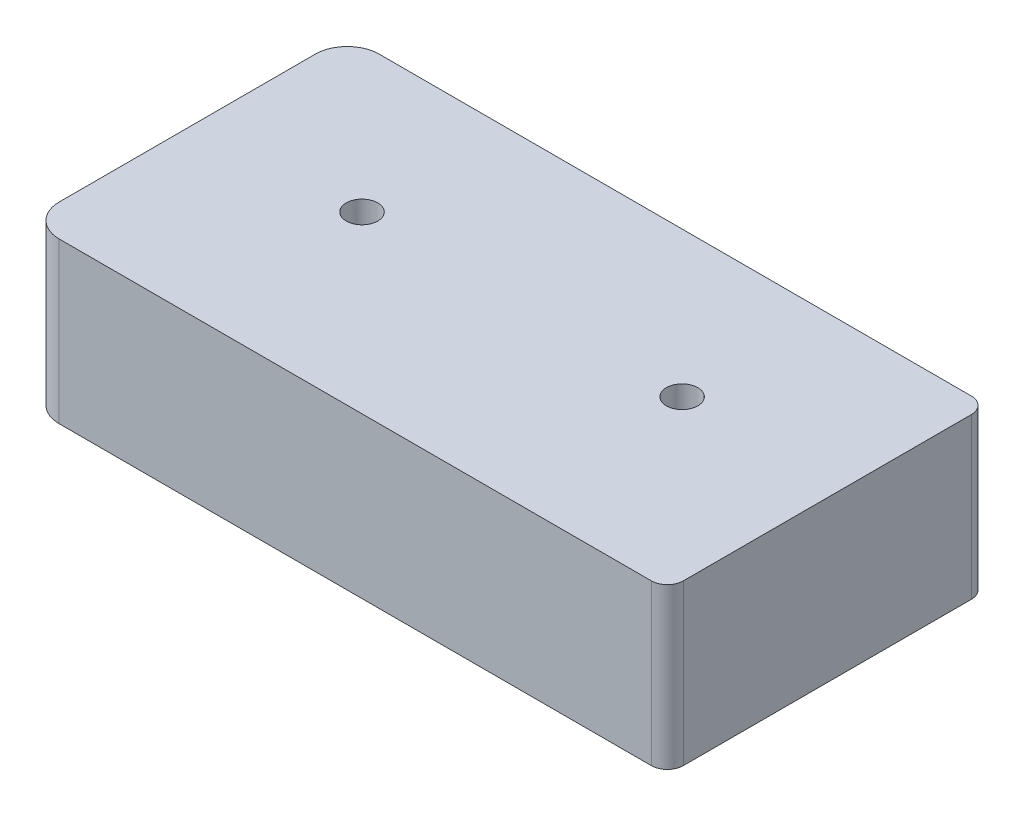
SolidWorks part; units mm, degrees
ref_plane "Front Plane" through (0, 0, 0) normal (0, 0, 1) x (1, 0, 0)
ref_plane "Top Plane" through (0, 0, 0) normal (0, 1, 0) x (1, 0, 0)
ref_plane "Right Plane" through (0, 0, 0) normal (1, 0, 0) x (0, 0, -1)
sketch "Sketch1" plane through (0, 0, 0) normal (0, 1, 0) x (1, 0, 0)
  line L1 (-50.8, 23.0573) -> (50.8, 23.0573)
  line L2 (-50.8, 23.0573) -> (-50.8, -27.7427)
  line L3 (-50.8, -27.7427) -> (50.8, -27.7427)
  line L4 (50.8, 23.0573) -> (50.8, -27.7427)
  point P4 (0, -27.7427)
  dimension "D1" = 50.8
  dimension "D2" = 101.6
extrude "Boss-Extrude1" add sketch "Sketch1" along normal blind 25.4
fillet "Fillet1" radius 5.08 2 edges at (-50.8, 12.7, 27.7427) (-50.8, 12.7, -23.0573)
fillet "Fillet2" radius 2.54 2 edges at (50.8, 12.7, 27.7427) (50.8, 12.7, -23.0573)
sketch "Sketch2" plane through (0, 25.4, 0) normal (0, 1, 0) x (1, 0, 0)
  line L0 (-50.8, 17.9773) -> (-50.8, -22.6627) construction
  line L1 (50.8, -25.2027) -> (50.8, 20.5173) construction
  circle A0 centre (-25.4, 0) radius 2.5
  circle A1 centre (25.4, 0) radius 2.5
  dimension "D1" = 5
  dimension "D2" = 25.4
  dimension ".7" = 25.4
extrude "Cut-Extrude1" cut sketch "Sketch2" against normal blind 25.4
